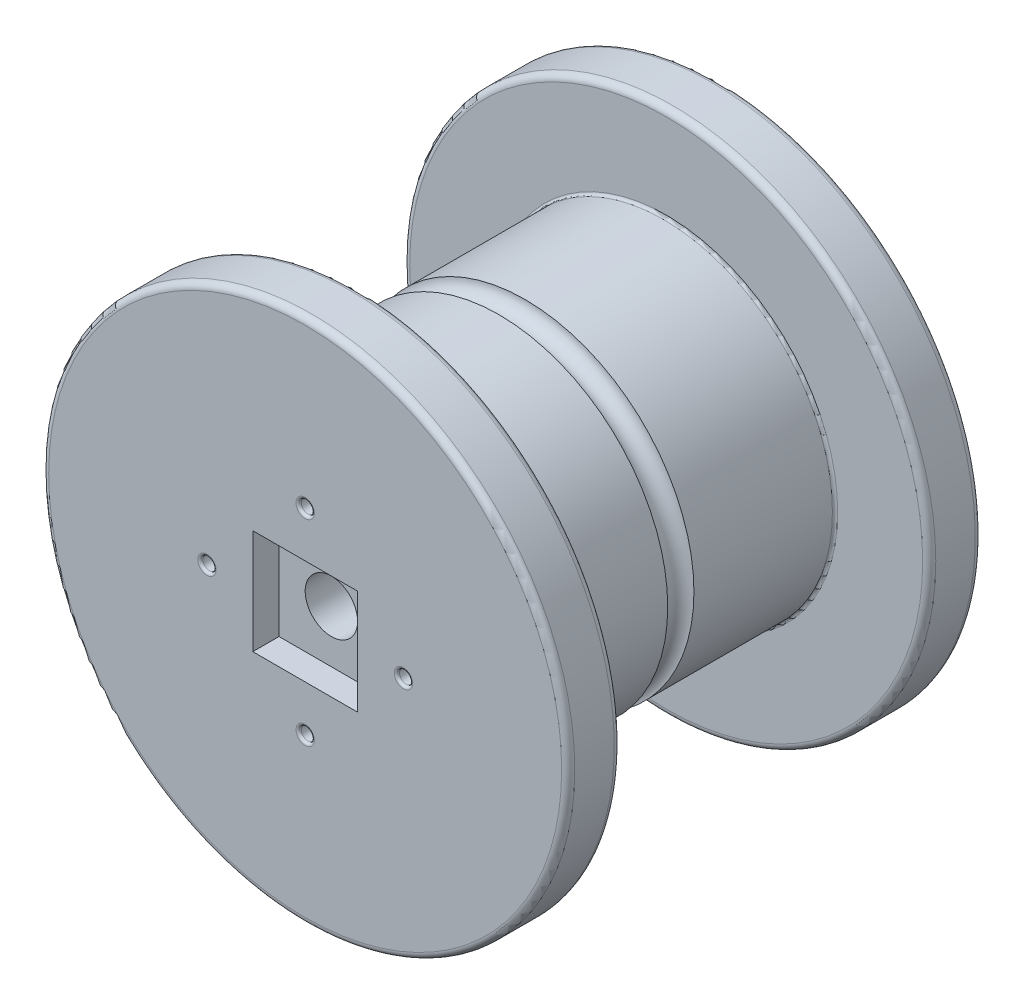
SolidWorks part; units mm, degrees
ref_plane "Front Plane" through (0, 0, 0) normal (0, 0, 1) x (1, 0, 0)
ref_plane "Top Plane" through (0, 0, 0) normal (0, 1, 0) x (1, 0, 0)
ref_plane "Right Plane" through (0, 0, 0) normal (1, 0, 0) x (0, 0, -1)
sketch "Sketch1" plane through (0, 0, 0) normal (1, 0, 0) x (0, 0, -1)
  line L0 (0, 0) -> (-189809.3465, 0) construction
  line L1 (-200.5, 19.05) -> (187.5, 19.05)
  line L2 (200.5, 44.45) -> (200.5, 255)
  line L3 (200.5, 255) -> (149.5, 255)
  line L4 (149.5, 255) -> (149.5, 163.6903)
  line L5 (149.5, 163.6903) -> (12.7, 163.6903)
  line L6 (-149.5, 163.6903) -> (-149.5, 255)
  line L7 (-149.5, 255) -> (-200.5, 255)
  line L8 (-200.5, 255) -> (-200.5, 19.05)
  line L9 (-12.7, 163.6903) -> (-149.5, 163.6903)
  line L14 (0, 0) -> (0, 50000) construction
  line L15 (175.1, 138.2903) -> (28.3981, 138.2903)
  line L16 (-28.3981, 138.2903) -> (-149.5, 138.2903)
  line L19 (149.5, 138.2903) -> (28.3981, 138.2903) construction
  line L22 (-149.5, 44.45) -> (-12.7, 44.45)
  line L23 (175.1, 69.85) -> (175.1, 138.2903)
  line L24 (-28.3981, 138.2903) -> (-149.5, 138.2903) construction
  line L25 (175.1, 44.45) -> (175.1, 255) construction
  line L26 (-175.1, 255) -> (-175.1, 44.45) construction
  line L27 (12.7, 127.7693) -> (12.7, 44.45)
  line L28 (-12.7, 127.7693) -> (-12.7, 44.45)
  line L29 (12.7, 44.45) -> (162.1, 44.45)
  line L30 (-175.1, 44.45) -> (175.1, 44.45) construction
  line L31 (200.5, 44.45) -> (187.5, 44.45)
  line L32 (187.5, 44.45) -> (187.5, 19.05)
  line L33 (200.5, 19.05) -> (200.5, 255) construction
  line L34 (-200.5, 19.05) -> (200.5, 19.05) construction
  line L35 (175.1, 69.85) -> (162.1, 69.85)
  line L36 (162.1, 69.85) -> (162.1, 44.45)
  line L37 (162.1, 69.85) -> (162.1, 19.05) construction
  line L38 (200.5, 69.85) -> (162.1, 69.85) construction
  line L39 (-149.5, 138.2903) -> (-149.5, 44.45)
  arc A0 (-12.7, 163.6903) -> (12.7, 163.6903) centre (0, 163.6903) ccw
  arc A1 (-28.3981, 138.2903) -> (-12.7, 127.7693) centre (0, 163.6903) ccw
  arc A2 (12.7, 127.7693) -> (28.3981, 138.2903) centre (0, 163.6903) ccw
  arc A3 (-28.3981, 138.2903) -> (28.3981, 138.2903) centre (0, 163.6903) ccw construction
  dimension "D6" = 12.7
  dimension "D1" = 51
  dimension "D3" = 255
  dimension "D4" = 163.6903
  dimension "D5" = 38.1
  dimension "D2" = 299
  dimension "D9" = 25.4
  dimension "D10" = 13
  dimension "D7" = 25.4
  dimension "D8" = 25.4
  dimension "D11" = 25.4
revolve "Revolve1" add sketch "Sketch1" angle 360 about L0
sketch "Sketch2" plane through (0, 0, 200.5) normal (0, 0, -1) x (-1, 0, 0)
  line L0 (50.8, 50.8) -> (-50.8, -50.8) construction
  line L1 (-50.8, -50.8) -> (50.8, -50.8)
  line L2 (-50.8, -50.8) -> (-50.8, 50.8)
  line L3 (-50.8, 50.8) -> (50.8, 50.8)
  line L4 (50.8, -50.8) -> (50.8, 50.8)
  dimension "D1" = 101.6
extrude "Cut-Extrude1" cut sketch "Sketch2" along normal blind 25.4
sketch "Sketch3" plane through (0, 0, 200.5) normal (0, 0, 1) x (1, 0, 0)
  line L0 (0, 0) -> (0, 95.25) construction
  circle A0 centre (0, 0) radius 25.4
  circle A2 centre (0, 95.25) radius 6.35
  dimension "D1" = 50.8
  dimension "D2" = 12.7
  dimension "D3" = 95.25
extrude "Cut-Extrude3" cut sketch "Sketch3" against normal through all
pattern_circular "CirPattern1" count 4 over 360 about axis through (0, 0, 0) along (0, 0, 1) of "Cut-Extrude3"
fillet "Fillet1" radius 6.35 4 edges at (-255, 0, -200.5) (-255, 0, -149.5) (-255, 0, 149.5) (-255, 0, 200.5)
fillet "Fillet2" radius 2.54 12 edges at (-6.35, -95.25, 200.5) (-95.25, 6.35, 200.5) (6.35, 95.25, 200.5) (95.25, -6.35, 200.5) (-95.25, 6.35, -200.5) (-6.35, -95.25, -200.5) (95.25, -6.35, -200.5) (6.35, 95.25, -200.5) (-44.45, 0, -187.5) (-44.45, 0, -200.5) (-163.6903, 0, -149.5) (-163.6903, 0, 149.5)
sketch "Sketch4" plane through (0, 0, 200.5) normal (0, 0, 1) x (1, 0, 0)
  line L0 (0, 0) -> (-7.2704, 317.5) construction
  line L1 (-35.2638, 290.1857) -> (-7.2704, 290.1857)
  line L2 (-35.2638, 290.1857) -> (-35.2638, 205.775)
  line L3 (-35.2638, 205.775) -> (-7.2704, 205.775)
  line L4 (-7.2704, 290.1857) -> (-7.2704, 205.775)
  circle A0 centre (-7.2704, 317.5) radius 25.019
  dimension "D2" = 50.038
  dimension "D1" = 317.5
equation "\"D4@Sketch1\"=12.889in/2"
equation "\"D5@Sketch1\"=3in/2"
equation "\"SP_wallOuterRadius\"= 255mm'does this even work"
equation "\"SP_length\"= 301mm'inner length"
equation "\"SP_sidewallWidth\"= 51mm"
equation "\"SP_boreDiameter\"= 13mm"
equation "\"D3@Sketch1\"=\"SP_wallOuterRadius\""
